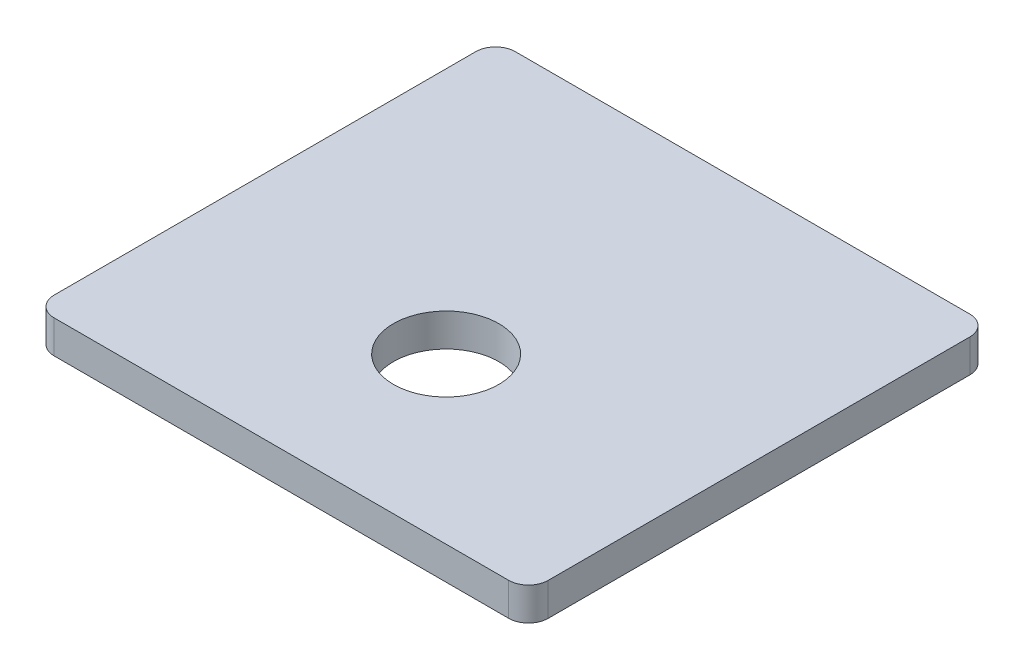
SolidWorks part; units mm, degrees
ref_plane "前视基准面" through (0, 0, 0) normal (0, 0, 1) x (1, 0, 0)
ref_plane "上视基准面" through (0, 0, 0) normal (0, 1, 0) x (1, 0, 0)
ref_plane "右视基准面" through (0, 0, 0) normal (1, 0, 0) x (0, 0, -1)
other "Configuration Table"
sketch "草图1" plane through (0, 0, 0) normal (0, 0, 1) x (1, 0, 0)
  line L0 (0, 0) -> (75, 0)
  line L1 (75, 0) -> (75, 5)
  line L2 (75, 5) -> (0, 5)
  line L3 (0, 5) -> (0, 0)
  dimension "width" = 75
  dimension "height" = 5
extrude "BlockExtrude" add sketch "草图1" along normal blind 70
fillet "Fillet" radius 3 4 edges at (0, 2.5, 0) (75, 2.5, 0) (0, 2.5, 70) (75, 2.5, 70)
sketch "草图2" plane through (0, 5, 0) normal (0, 1, 0) x (1, 0, 0)
  circle A0 centre (37.5, -45) radius 8
  dimension "diameter" = 16
  dimension "x" = 37.5
  dimension "y" = 45
extrude "Rotary_seal_seat" cut sketch "草图2" against normal through all
